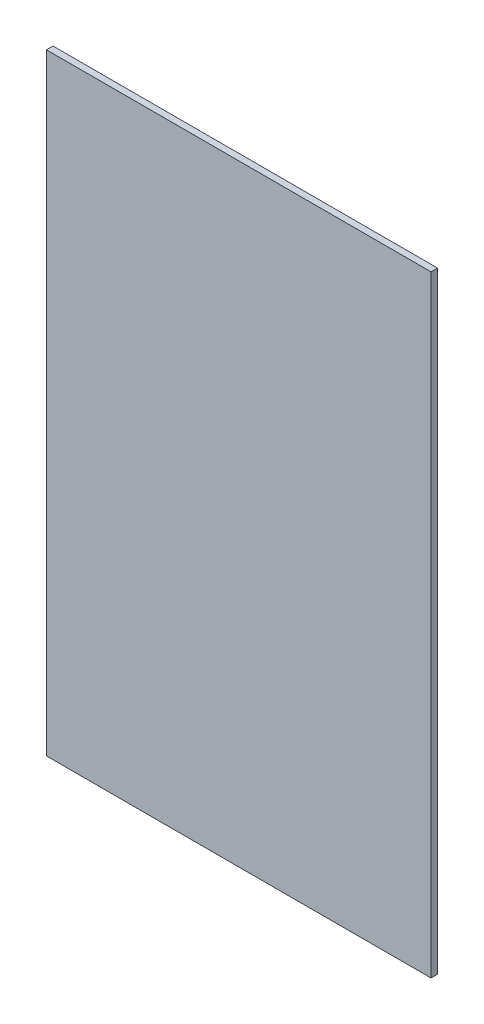
SolidWorks part; units mm, degrees
ref_plane "Front Plane" through (0, 0, 0) normal (0, 0, 1) x (1, 0, 0)
ref_plane "Top Plane" through (0, 0, 0) normal (0, 1, 0) x (1, 0, 0)
ref_plane "Right Plane" through (0, 0, 0) normal (1, 0, 0) x (0, 0, -1)
sketch "Sketch1" plane through (0, 0, 0) normal (0, 0, 1) x (1, 0, 0)
  line L0 (-284.5572, -60.7822) -> (-80.8355, -60.7822) construction
  line L1 (-99.8992, -60.7822) -> (49.2125, -60.7822)
  line L2 (-99.8992, -60.7822) -> (-99.8992, -297.8658)
  line L3 (-99.8992, -297.8658) -> (49.2125, -297.8658)
  line L4 (49.2125, -60.7822) -> (49.2125, -297.8658)
  point P4 (-99.9626, -60.7822)
  point P9 (46.0213, -300.6707)
  point P10 (0, 0)
extrude "Boss-Extrude1" add sketch "Sketch1" along normal blind 2.54
